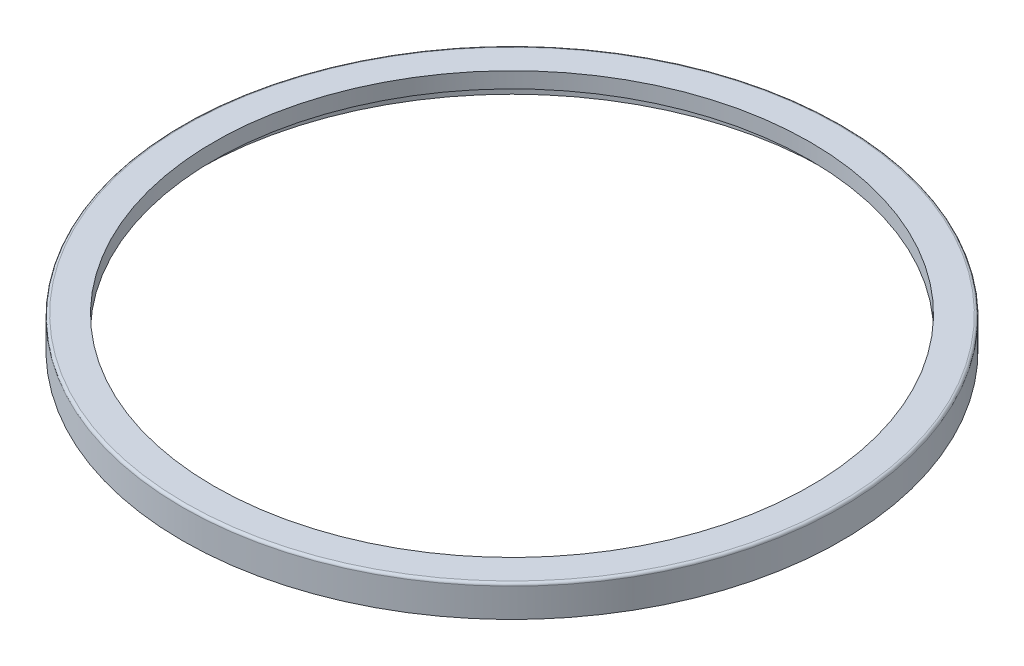
SolidWorks part; units mm, degrees
material "AISI 4340 Steel, annealed"
ref_plane "Front Plane" through (0, 0, 0) normal (0, 0, 1) x (1, 0, 0)
ref_plane "Top Plane" through (0, 0, 0) normal (0, 1, 0) x (1, 0, 0)
ref_plane "Right Plane" through (0, 0, 0) normal (1, 0, 0) x (0, 0, -1)
sketch "Sketch1" plane through (0, 0, 0) normal (0, 0, 1) x (1, 0, 0)
  line L0 (0, 0) -> (-57.7215, 0) construction
  line L1 (0, 0) -> (0, 16.6258) construction
  line L2 (-57.7215, 0) -> (-63.8175, 0)
  line L3 (-63.8175, 0) -> (-63.8175, -6.096)
  line L4 (-63.8175, -6.096) -> (-60.7695, -6.096)
  line L5 (-60.7695, -6.096) -> (-60.7695, -3.048)
  line L6 (-60.7695, -3.048) -> (-57.7215, -3.048)
  line L7 (-57.7215, -3.048) -> (-57.7215, 0)
  dimension "D1" = 63.8175
  dimension "D2" = 3.048
  dimension "D3" = 6.096
  dimension "D4" = 3.048
  dimension "D5" = 6.096
revolve "Revolve1" add sketch "Sketch1" angle 360 about L1
fillet "Fillet1" radius 1.5875 1 edges at (0, -3.048, -60.7695)
fillet "Fillet2" radius 0.508 1 edges at (0, 0, -63.8175)
